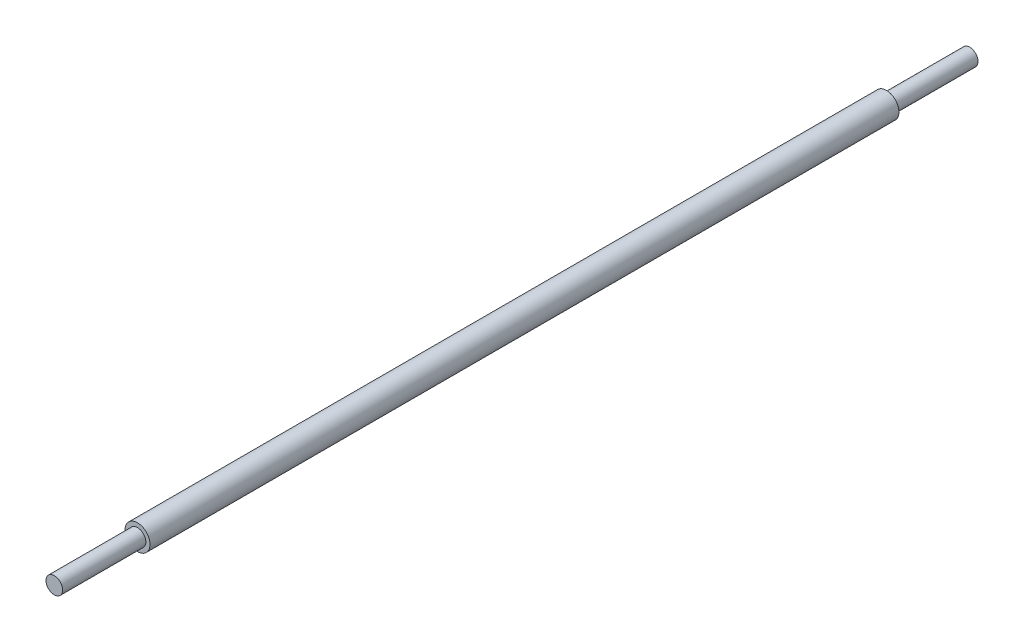
SolidWorks part; units mm, degrees
ref_plane "Alzado" through (0, 0, 0) normal (0, 0, 1) x (1, 0, 0)
ref_plane "Planta" through (0, 0, 0) normal (0, 1, 0) x (1, 0, 0)
ref_plane "Vista lateral" through (0, 0, 0) normal (1, 0, 0) x (0, 0, -1)
sketch "Croquis1" plane through (0, 0, 0) normal (0, 0, 1) x (1, 0, 0)
  circle A0 centre (0, 0) radius 6
extrude "Saliente-Extruir1" add sketch "Croquis1" along normal blind 400 contours A0
sketch "Croquis2" plane through (0, 0, 400) normal (0, 0, 1) x (1, 0, 0)
  circle A0 centre (0, 0) radius 6
  circle A1 centre (0, 0) radius 4
extrude "Cortar-Extruir3" cut sketch "Croquis2" against normal blind 40 flip side to cut contours A1
sketch "Croquis3" plane through (0, 0, 0) normal (0, 0, -1) x (-1, 0, 0)
  circle A0 centre (0, 0) radius 4
  dimension "D1" = 8
extrude "Saliente-Extruir2" add sketch "Croquis3" along normal blind 40
